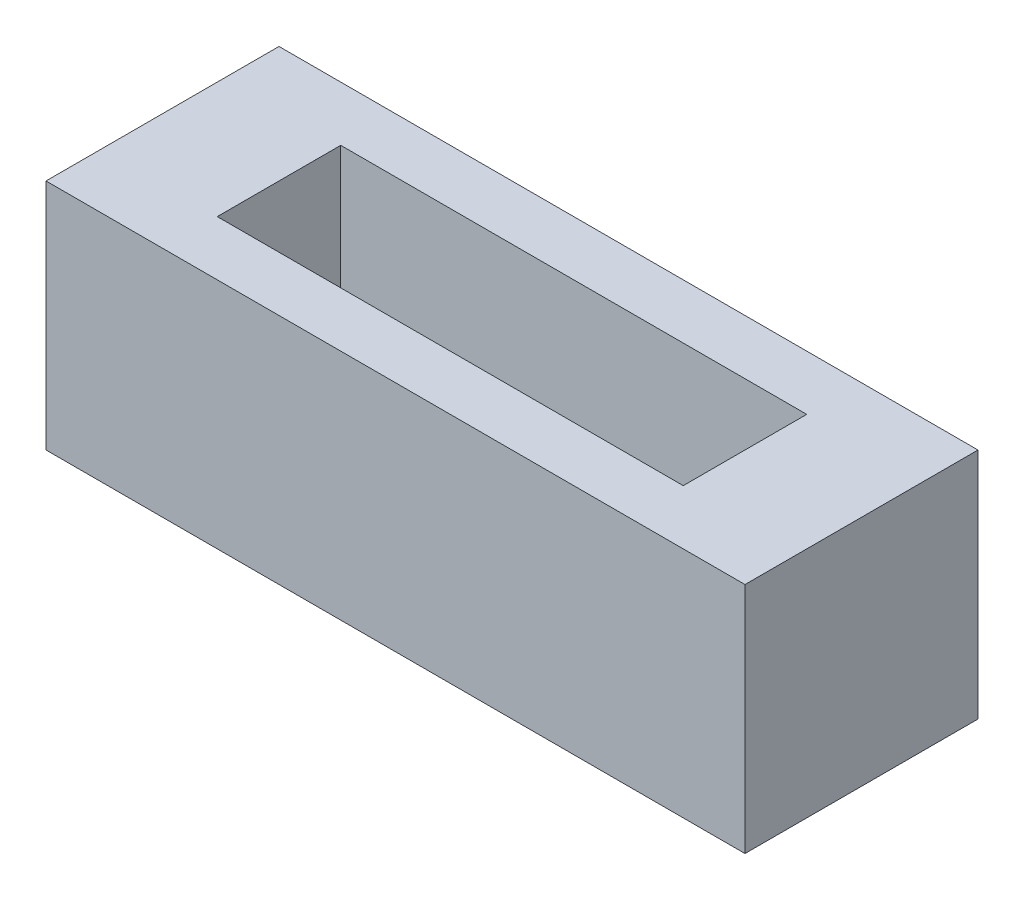
SolidWorks part; units mm, degrees
ref_plane "Front Plane" through (0, 0, 0) normal (0, 0, 1) x (1, 0, 0)
ref_plane "Top Plane" through (0, 0, 0) normal (0, 1, 0) x (1, 0, 0)
ref_plane "Right Plane" through (0, 0, 0) normal (1, 0, 0) x (0, 0, -1)
sketch "Sketch1" plane through (0, 0, 0) normal (0, 1, 0) x (1, 0, 0)
  line L1 (-19.05, -6.35) -> (19.05, -6.35)
  line L2 (-19.05, -6.35) -> (-19.05, 6.35)
  line L3 (-19.05, 6.35) -> (19.05, 6.35)
  line L4 (19.05, -6.35) -> (19.05, 6.35)
  line L5 (-19.05, -6.35) -> (19.05, 6.35) construction
  line L6 (-19.05, 6.35) -> (19.05, -6.35) construction
  point P0 (0, 0)
  dimension "D1" = 12.7
  dimension "D2" = 38.1
extrude "Boss-Extrude1" add sketch "Sketch1" along normal blind 12.7
sketch "Sketch2" plane through (0, 12.7, 0) normal (0, 1, 0) x (1, 0, 0)
  line L1 (-12.7, -3.3655) -> (12.7, -3.3655)
  line L2 (-12.7, -3.3655) -> (-12.7, 3.3655)
  line L3 (-12.7, 3.3655) -> (12.7, 3.3655)
  line L4 (12.7, -3.3655) -> (12.7, 3.3655)
  line L5 (-12.7, -3.3655) -> (12.7, 3.3655) construction
  line L6 (-12.7, 3.3655) -> (12.7, -3.3655) construction
  point P0 (0, 0)
  dimension "D1" = 6.731
  dimension "D2" = 25.4
extrude "Cut-Extrude1" cut sketch "Sketch2" against normal blind 12.7
